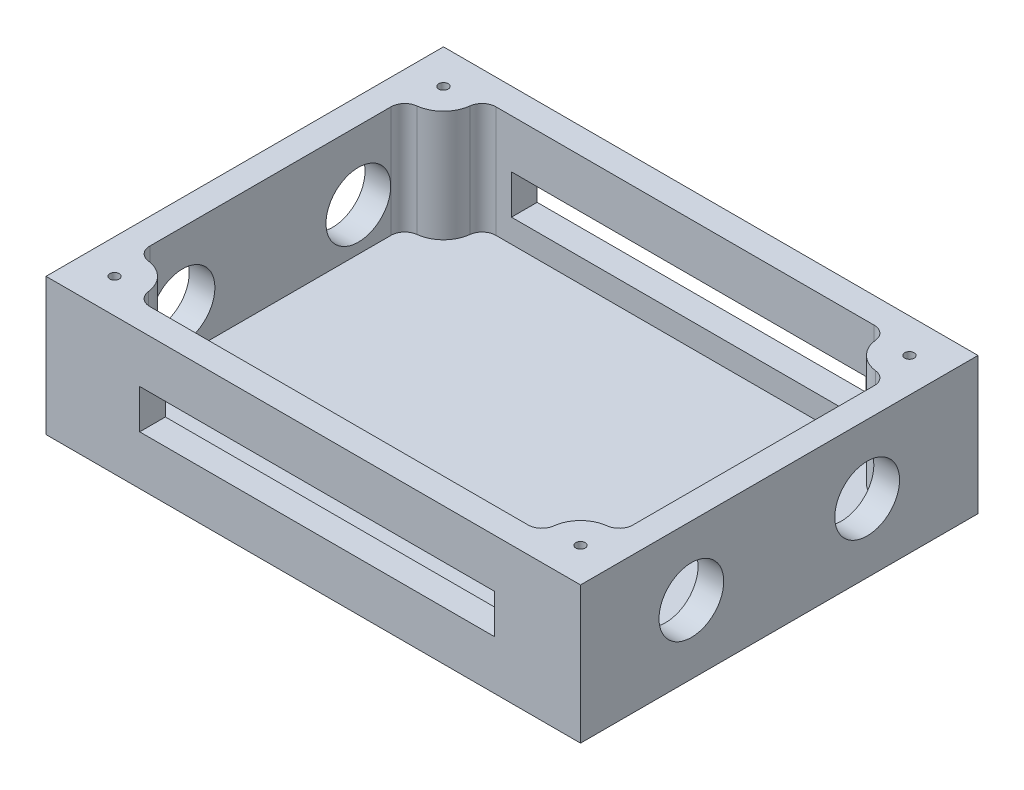
SolidWorks part; units mm, degrees
ref_plane "Front Plane" through (0, 0, 0) normal (0, 0, 1) x (1, 0, 0)
ref_plane "Top Plane" through (0, 0, 0) normal (0, 1, 0) x (1, 0, 0)
ref_plane "Right Plane" through (0, 0, 0) normal (1, 0, 0) x (0, 0, -1)
sketch "Sketch1" plane through (0, 0, 0) normal (0, 1, 0) x (1, 0, 0)
  line L1 (49.53, -36.83) -> (-49.53, -36.83)
  line L2 (49.53, -36.83) -> (49.53, 36.83)
  line L3 (49.53, 36.83) -> (-49.53, 36.83)
  line L4 (-49.53, -36.83) -> (-49.53, 36.83)
  line L5 (49.53, -36.83) -> (-49.53, 36.83) construction
  line L6 (49.53, 36.83) -> (-49.53, -36.83) construction
  point P0 (0, 0)
  dimension "D1" = 99.06
  dimension "D2" = 73.66
extrude "Boss-Extrude1" add sketch "Sketch1" along normal blind 25.4
sketch "Sketch2" plane through (0, 25.4, 0) normal (0, 1, 0) x (1, 0, 0)
  line L0 (49.53, 36.83) -> (-49.53, 36.83) construction
  line L1 (43.18, -30.48) -> (-43.18, -30.48) construction
  line L2 (43.18, -30.48) -> (43.18, 30.48) construction
  line L3 (43.18, 30.48) -> (-43.18, 30.48) construction
  line L4 (-43.18, -30.48) -> (-43.18, 30.48) construction
  line L5 (43.18, -30.48) -> (-43.18, 30.48) construction
  line L6 (43.18, 30.48) -> (-43.18, -30.48) construction
  line L7 (-49.53, 36.83) -> (-49.53, -36.83) construction
  point P0 (0, 0)
  point P11 (-43.18, 30.48)
  point P13 (-43.18, -30.48)
  point P15 (43.18, -30.48)
  point P17 (43.18, 30.48)
  dimension "D1" = 6.35
  dimension "D2" = 6.35
hole_wizard "M2.2x0.45 Tapped Hole2" positions "Sketch8" profile "Sketch9" tap size "M2.2x0.45" standard "ANSI Metric"
sketch "Sketch8" plane through (0, 25.4, 0) normal (0, 1, 0) x (1, 0, 0)
  point P0 (-43.18, 30.48)
  point P3 (43.18, 30.48)
  point P6 (43.18, -30.48)
  point P9 (-43.18, -30.48)
sketch "Sketch9" plane through (-43.18, 25.4, -30.48) normal (1, 0, 0) x (0, 0, 1)
  line L0 (0, 0) -> (0, 31.0058)
  line L1 (0, 31.0058) -> (0.875, 30.48)
  line L2 (0.875, 30.48) -> (0.875, 0)
  line L5 (0.875, 0) -> (0, 0)
  line L10 (0, 31.0058) -> (-0.875, 30.48) construction
  line L11 (0, -6.35) -> (0, 107.95) construction
  dimension "Tap Drill Dia." = 1.75
  dimension "Tap Drill Depth" = 30.48
  dimension "Drill Angle" = 118
cosmetic thread "Hole Thread11" parameters "D1"=4.4, "D2"=2.2
cosmetic thread "Hole Thread12" parameters "D1"=4.4, "D2"=2.2
cosmetic thread "Hole Thread13" parameters "D1"=4.4, "D2"=2.2
cosmetic thread "Hole Thread14" parameters "D1"=4.4, "D2"=2.2
shell "Shell3" thickness 4.7625
fillet "Fillet2" radius 2.54 8 edges at (-44.7675, 15.0813, 25.0706) (-37.7706, 15.0813, 32.0675) (37.7706, 15.0813, 32.0675) (44.7675, 15.0813, 25.0706) (44.7675, 15.0813, -25.0706) (37.7706, 15.0813, -32.0675) (-44.7675, 15.0813, -25.0706) (-37.7706, 15.0813, -32.0675)
sketch "Sketch11" plane through (49.53, 0, 0) normal (1, 0, 0) x (0, 0, -1)
  line L0 (-22.2748, 25.4) -> (-22.2748, 0) construction
  line L1 (-36.83, 25.4) -> (36.83, 25.4) construction
  line L2 (-36.83, 0) -> (36.83, 0) construction
  line L3 (24.4204, 25.4) -> (24.4204, 0) construction
  line L4 (-36.83, 25.4) -> (-36.83, 0) construction
  line L5 (36.83, 25.4) -> (36.83, 0) construction
  circle A0 centre (-16.2906, 12.7) radius 6
  circle A1 centre (16.2906, 12.7) radius 6
  point P0 (-22.2748, 26.9043)
  point P1 (24.4204, 26.9043)
  point P16 (-36.83, 12.7)
  dimension "D1" = 12
  dimension "D2" = 12
  dimension "D3" = 20.5394
  dimension "D4" = 20.5394
extrude "Cut-Extrude1" cut sketch "Sketch11" against normal through all both and the other way through all
sketch "Sketch12" plane through (0, 0, -36.83) normal (0, 0, -1) x (-1, 0, 0)
  line L0 (-43.18, 25.4) -> (43.18, 25.4) construction
  line L1 (32.1675, 9.1199) -> (-33.5568, 9.1199)
  line L2 (32.1675, 9.1199) -> (32.1675, 16.4)
  line L3 (32.1675, 16.4) -> (-33.5568, 16.4)
  line L4 (-33.5568, 9.1199) -> (-33.5568, 16.4)
  line L5 (32.1675, 9.1199) -> (-33.5568, 16.4) construction
  line L6 (32.1675, 16.4) -> (-33.5568, 9.1199) construction
  point P0 (-0.6946, 12.7599)
  point P7 (-33.5568, 16.4)
  point P8 (0, 0)
  point P9 (34.6255, 16.4)
  point P10 (0, 0)
  point P11 (32.1675, 9.1199)
  dimension "D1" = 9
extrude "Cut-Extrude2" cut sketch "Sketch12" against normal through all both and the other way through all
equation "\"D2@Sketch2\"=\"D1@Sketch2\""
equation "\"D2@Sketch11\"=\"D1@Sketch11\""
equation "\"D4@Sketch11\"=\"D3@Sketch11\""
